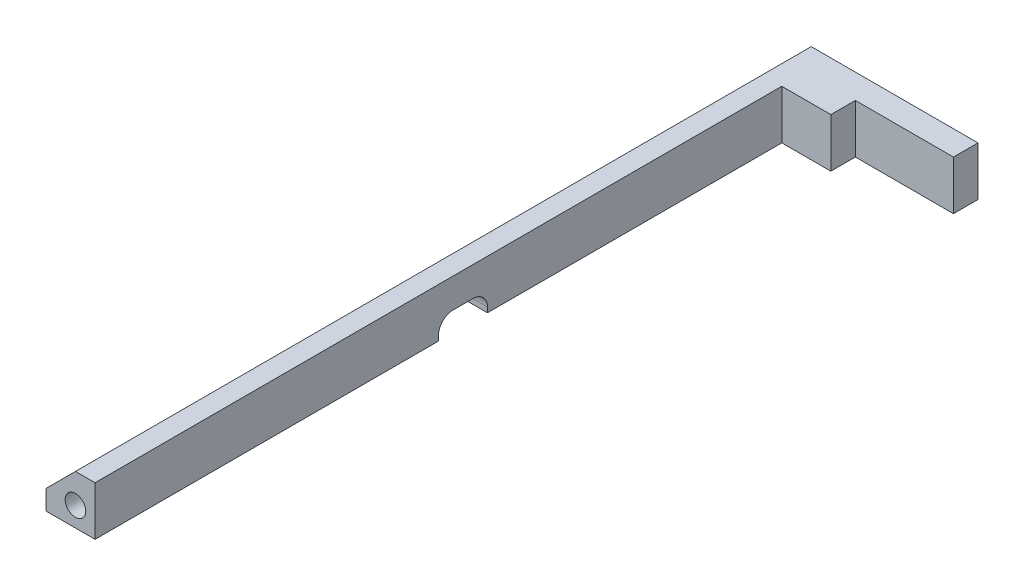
SolidWorks part; units mm, degrees
material "ABS"
ref_plane "Płaszczyzna przednia" through (0, 0, 0) normal (0, 0, 1) x (1, 0, 0)
ref_plane "Płaszczyzna górna" through (0, 0, 0) normal (0, 1, 0) x (1, 0, 0)
ref_plane "Płaszczyzna prawa" through (0, 0, 0) normal (1, 0, 0) x (0, 0, -1)
sketch "Szkic1" plane through (0, 0, 0) normal (0, 1, 0) x (1, 0, 0)
  line L0 (0, 0) -> (0, 150)
  line L1 (0, 150) -> (40, 150)
  line L2 (40, 150) -> (40, 145)
  line L3 (40, 145) -> (20, 145)
  line L4 (20, 145) -> (20, 140)
  line L5 (20, 140) -> (10, 140)
  line L6 (10, 140) -> (10, 0)
  line L7 (10, 0) -> (0, 0)
  dimension "D1" = 140
  dimension "D2" = 5
  dimension "D3" = 5
  dimension "D5" = 10
  dimension "D6" = 10
  dimension "D4" = 20
extrude "Dodanie-wyciągnięcie1" add sketch "Szkic1" along normal blind 10
sketch "Szkic2" plane through (0, 0, 0) normal (0, -1, 0) x (1, 0, 0)
  line L0 (0, 0) -> (0, -27) construction
  line L1 (0, -150) -> (0, 0) construction
  line L2 (0, -27) -> (7.2, -27) construction
  line L3 (7.2, -27) -> (7.2, -123) construction
  circle A0 centre (7.2, -27) radius 2.1
  circle A1 centre (7.2, -123) radius 2.1
  dimension "D2" = 4.2
  dimension "D4" = 4.2
  dimension "D1" = 27
  dimension "D3" = 96
  dimension "D5" = 7.2
extrude "Wytnij-wyciągnięcie1" cut sketch "Szkic2" against normal blind 4
sketch "Szkic3" plane through (0, 0, 0) normal (0, 0, 1) x (1, 0, 0)
  line L0 (0, 0) -> (6, 0) construction
  line L1 (0, 0) -> (10, 0) construction
  line L2 (6, 0) -> (6, 4) construction
  circle A0 centre (6, 4) radius 2.1
  dimension "D3" = 4.2
  dimension "D1" = 6
  dimension "D2" = 4
extrude "Wytnij-wyciągnięcie2" cut sketch "Szkic3" against normal blind 4
chamfer "Sfazowanie1" distance 6 angle 45 1 edges at (0, 10, -75)
sketch "Szkic4" plane through (0, 0, 0) normal (0, -1, 0) x (1, 0, 0)
  line L0 (0, 0) -> (0, -75) construction
  line L1 (0, -150) -> (0, 0) construction
  line L7 (0, -70) -> (0, -80)
  line L8 (0, -80) -> (10, -80)
  line L9 (10, 0) -> (10, -140) construction
  line L10 (10, -80) -> (10, -70)
  line L11 (10, -70) -> (0, -70)
  point P8 (0, -75)
  dimension "D2" = 75
  dimension "D1" = 10
extrude "Wytnij-wyciągnięcie3" cut sketch "Szkic4" against normal blind 4
fillet "Zaokrąglenie1" radius 3 2 edges at (5, 4, -70) (5, 4, -80)
equation "\"Length\"=140"
equation "\"D1@Szkic1\"=\"Length\""
equation "\"Width\"=10"
equation "\"D6@Szkic1\"=\"Width\""
equation "\"D3@Szkic1\"=\"Width\"/2"
equation "\"D2@Szkic1\"=\"Width\"/2"
equation "\"D1@Szkic2\"=(\"Length\"+\"Width\"-96)/2"
equation "\"InsertDiameter\"=4.2"
equation "\"D2@Szkic2\"=\"InsertDiameter\""
equation "\"D4@Szkic2\"=\"InsertDiameter\""
equation "\"D3@Szkic3\"=\"InsertDiameter\""
equation "\"D1@Szkic3\"=\"Width\"/2+1"
equation "\"D2@Szkic3\"=\"Width\"/2-1"
equation "\"StrapSize\"=10"
equation "\"D2@Szkic4\"=(\"Length\"+\"Width\")/2"
equation "\"D1@Szkic4\"=\"StrapSize\""
